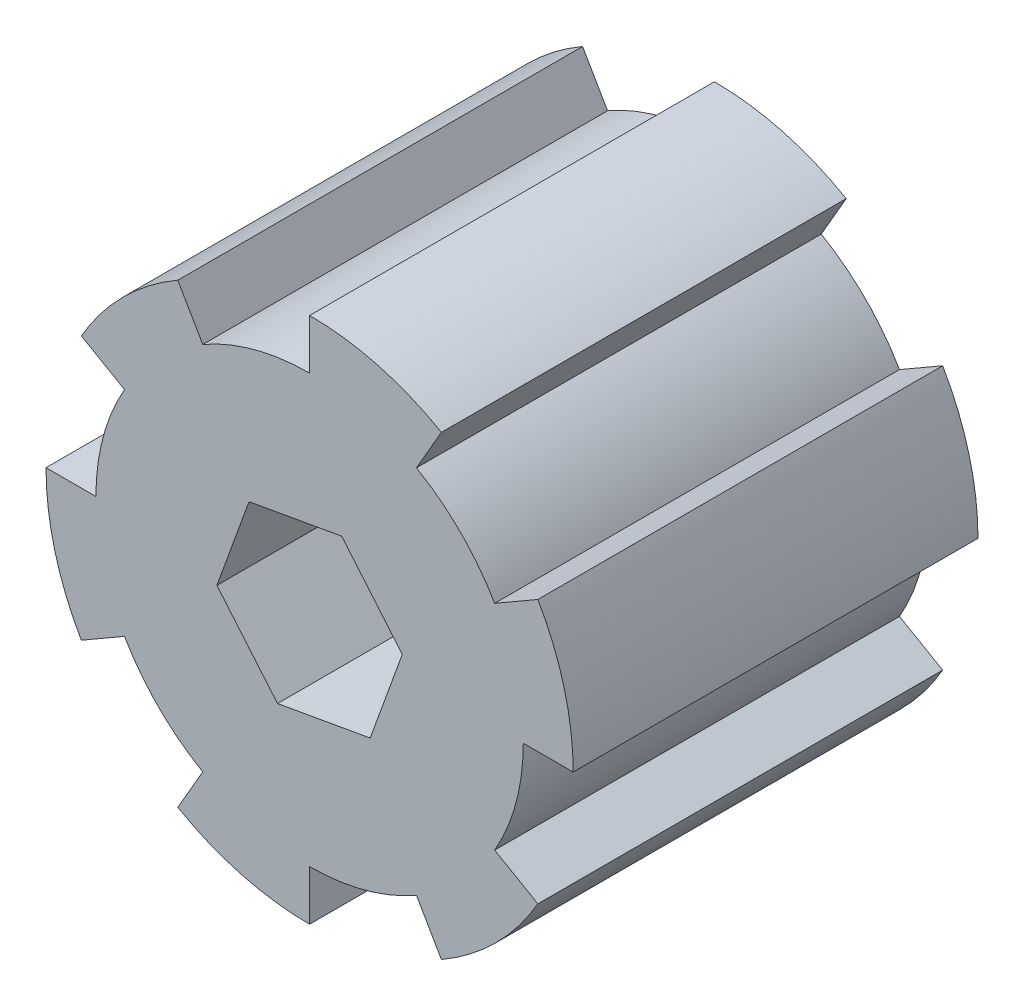
SolidWorks part; units mm, degrees
ref_plane "Płaszczyzna przednia" through (0, 0, 0) normal (0, 0, 1) x (1, 0, 0)
ref_plane "Płaszczyzna górna" through (0, 0, 0) normal (0, 1, 0) x (1, 0, 0)
ref_plane "Płaszczyzna prawa" through (0, 0, 0) normal (1, 0, 0) x (0, 0, -1)
sketch "Szkic1" plane through (0, 0, 0) normal (0, 0, 1) x (1, 0, 0)
  line L0 (0, 14) -> (0, 11.35)
  line L1 (-7, 12.1244) -> (-5.675, 9.8294)
  line L2 (14, 0) -> (11.35, 0)
  line L3 (12.1244, -7) -> (9.8294, -5.675)
  line L4 (12.1244, 7) -> (9.8294, 5.675)
  line L5 (-7, -12.1244) -> (-5.675, -9.8294)
  line L6 (5.675, -9.8294) -> (7, -12.1244)
  line L7 (-9.8294, 5.675) -> (-12.1244, 7)
  line L8 (-11.35, 0) -> (-14, 0)
  line L9 (-9.8294, -5.675) -> (-12.1244, -7)
  line L10 (5.675, 9.8294) -> (7, 12.1244)
  line L11 (0, -11.35) -> (0, -14)
  line L13 (4.923, 0.8741) -> (1.7045, 4.7005)
  line L14 (1.7045, 4.7005) -> (-3.2185, 3.8264)
  line L15 (-3.2185, 3.8264) -> (-4.923, -0.8741)
  line L16 (-4.923, -0.8741) -> (-1.7045, -4.7005)
  line L17 (-1.7045, -4.7005) -> (3.2185, -3.8264)
  line L18 (3.2185, -3.8264) -> (4.923, 0.8741)
  arc A0 (-7, 12.1244) -> (-12.1244, 7) centre (0, 0) ccw
  arc A1 (-9.8294, 5.675) -> (-11.35, 0) centre (0, 0) ccw
  arc A2 (-14, 0) -> (-12.1244, -7) centre (0, 0) ccw
  arc A3 (-7, -12.1244) -> (0, -14) centre (0, 0) ccw
  arc A4 (7, -12.1244) -> (12.1244, -7) centre (0, 0) ccw
  arc A5 (14, 0) -> (12.1244, 7) centre (0, 0) ccw
  arc A6 (7, 12.1244) -> (0, 14) centre (0, 0) ccw
  arc A7 (0, 11.35) -> (-5.675, 9.8294) centre (0, 0) ccw
  arc A8 (9.8294, 5.675) -> (5.675, 9.8294) centre (0, 0) ccw
  arc A9 (9.8294, -5.675) -> (11.35, 0) centre (0, 0) ccw
  arc A10 (0, -11.35) -> (5.675, -9.8294) centre (0, 0) ccw
  arc A11 (-9.8294, -5.675) -> (-5.675, -9.8294) centre (0, 0) ccw
  circle A12 centre (0, 0) radius 4.3301 construction
  circle A13 centre (0, 0) radius 5 construction
  dimension "D2" = 28
  dimension "D3" = 22.7
  dimension "D7" = 10
  dimension "D1" = 30
  dimension "D4" = 30
  dimension "D5" = 30
  dimension "D6" = 30
extrude "Dodanie-wyciągnięcie1" add sketch "Szkic1" along normal blind 21.5
